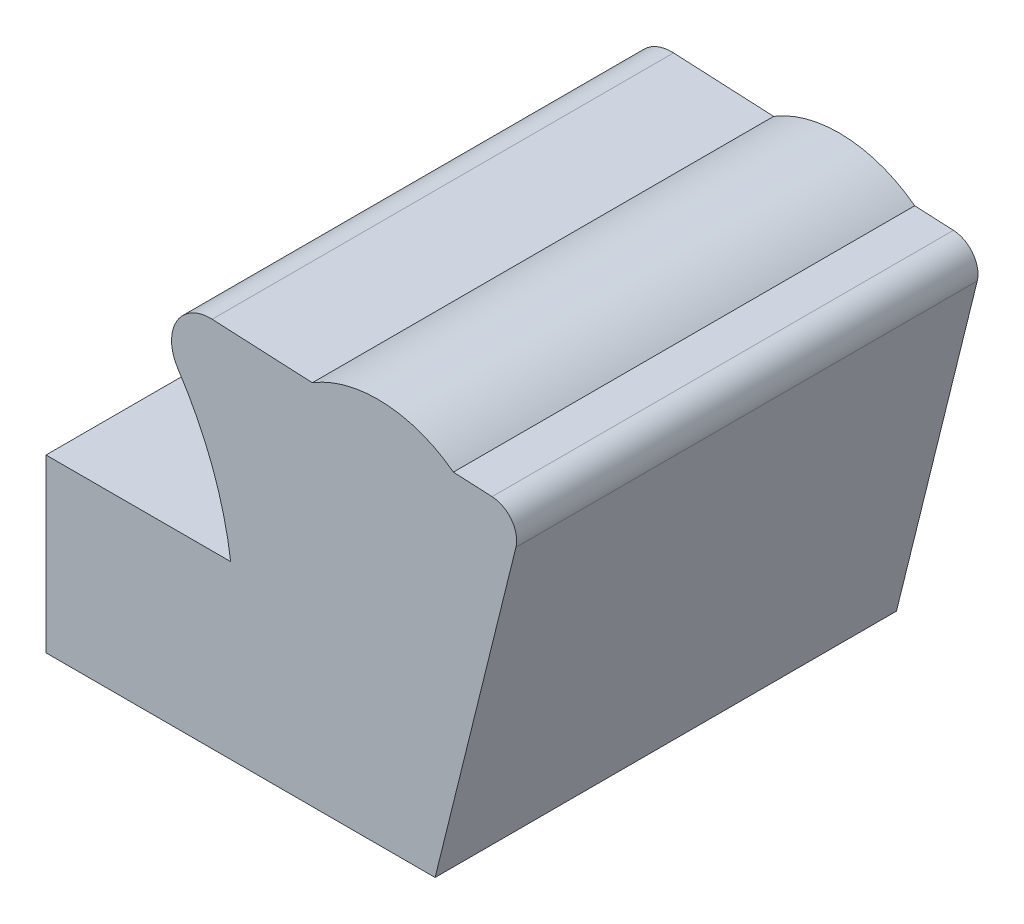
SolidWorks part; units mm, degrees
ref_plane "前视基准面" through (0, 0, 0) normal (0, 0, 1) x (1, 0, 0)
ref_plane "上视基准面" through (0, 0, 0) normal (0, 1, 0) x (1, 0, 0)
ref_plane "右视基准面" through (0, 0, 0) normal (1, 0, 0) x (0, 0, -1)
sketch "草图2" plane through (0, 0, 0) normal (0, 0, 1) x (1, 0, 0)
  line L0 (136.6039, 47.5616) -> (154.1159, 118.2938)
  line L1 (52.2591, 37.348) -> (26.1206, 28.5308)
  line L2 (148.9533, 125.233) -> (88.2808, 128.1975)
  line L3 (0, 28.5308) -> (0, 0)
  line L5 (0, 0) -> (140.98, 0)
  line L6 (26.1206, 28.5308) -> (0, 28.5308)
  line L7 (87.78, 14.3923) -> (87.78, 0) construction
  line L12 (131.9282, 26.834) -> (115.25, 26.834)
  line L13 (120.3818, 47.5616) -> (136.6039, 47.5616)
  line L14 (115.25, 26.834) -> (120.3818, 47.5616)
  line L15 (52.2591, 84.7067) -> (92.2882, 84.7067)
  line L18 (52.2591, 84.7067) -> (52.2591, 37.348)
  line L21 (140.98, 0) -> (131.9282, 26.834)
  line L23 (87.8709, 119.8075) -> (124.18, 103.95) construction
  arc A3 (88.2808, 128.1975) -> (80.8637, 115.1752) centre (87.8709, 119.8075) ccw
  circle A8 centre (124.18, 103.95) radius 27.1849
  arc A11 (92.2882, 84.7067) -> (80.8637, 115.1752) centre (20.1345, 75.0279) ccw
  arc A12 (154.1159, 118.2938) -> (148.9533, 125.233) centre (148.68, 119.6396) ccw
  point P0 (0, 0)
  dimension "D1" = 54.3698
  dimension "D2" = 8.4
  dimension "D3" = 72.8
  dimension "D4" = 5.6
  dimension "D5" = 20.1345
  dimension "D6" = 26.1206
  dimension "D7" = 52.2591
  dimension "D8" = 80.8637
  dimension "D9" = 87.78
  dimension "D10" = 88.2808
  dimension "D11" = 148.68
  dimension "D12" = 92.2882
  dimension "D13" = 115.25
  dimension "D14" = 120.3818
  dimension "D15" = 124.18
  dimension "D16" = 131.9282
  dimension "D17" = 136.6039
  dimension "D18" = 140.98
  dimension "D19" = 26.834
  dimension "D20" = 28.5308
  dimension "D21" = 154.1159
  dimension "D26" = 103.95
extrude "凸台-拉伸1" add sketch "草图2" along normal mid plane 100 contours A11 L15 L18 L1 L6 L3 L5 L21 L12 L14 L13 L0 A8 L2 A3 | L0 A8 L2 | L2 A8 | L0 A12 L2 A8
sketch "草图3" plane through (0, 0, 50) normal (0, 0, 1) x (1, 0, 0)
  line L0 (120.3818, 47.5616) -> (52.2591, 47.5616)
  line L1 (52.2591, 84.7067) -> (52.2591, 37.348) construction
split "分割1" trim tools "草图3" bodies to split 106 resulting bodies 107 108
delete or keep bodies "实体-删除/保留 1" type keep bodies bodies 107
